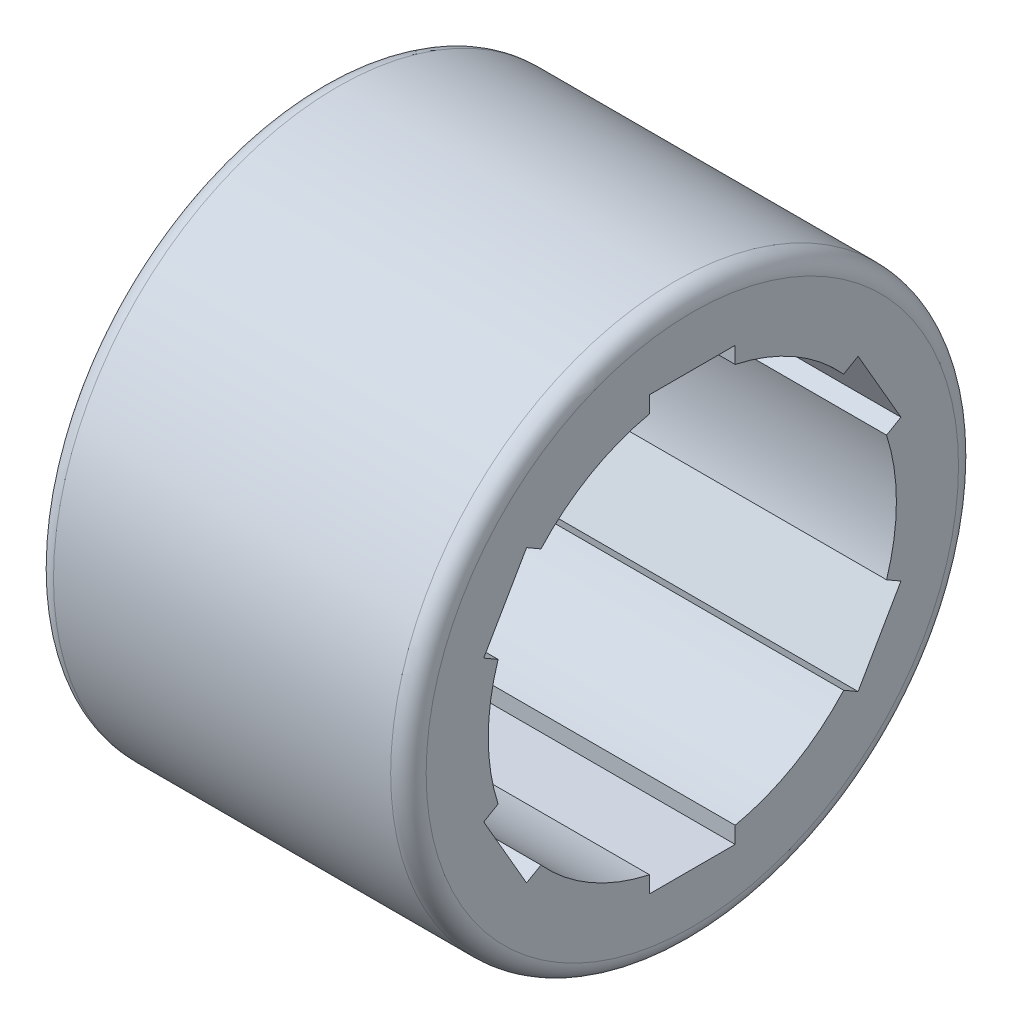
SolidWorks part; units mm, degrees
ref_plane "Front" through (0, 0, 0) normal (0, 0, 1) x (1, 0, 0)
ref_plane "Top" through (0, 0, 0) normal (0, 1, 0) x (1, 0, 0)
ref_plane "Right" through (0, 0, 0) normal (1, 0, 0) x (0, 0, -1)
sketch "Croquis1" plane through (0, 0, 0) normal (1, 0, 0) x (0, 0, -1)
  line L0 (0, 19.3057) -> (0, 12.18) construction
  line L1 (9.3407, 8.1815) -> (11.7557, 3.9985)
  line L3 (-2.415, 11.2436) -> (-2.415, 12.18)
  line L4 (-2.415, 12.18) -> (2.415, 12.18)
  line L5 (2.415, 11.2436) -> (2.415, 12.18)
  line L8 (8.5297, 7.7132) -> (9.3407, 8.1815)
  line L10 (10.9447, 3.5303) -> (11.7557, 3.9985)
  line L11 (11.7557, -3.9985) -> (9.3407, -8.1815)
  line L12 (10.9447, -3.5303) -> (11.7557, -3.9985)
  line L14 (8.5297, -7.7132) -> (9.3407, -8.1815)
  line L15 (2.415, -12.18) -> (-2.415, -12.18)
  line L16 (2.415, -11.2436) -> (2.415, -12.18)
  line L18 (-2.415, -11.2436) -> (-2.415, -12.18)
  line L19 (-9.3407, -8.1815) -> (-11.7557, -3.9985)
  line L20 (-8.5297, -7.7132) -> (-9.3407, -8.1815)
  line L22 (-10.9447, -3.5303) -> (-11.7557, -3.9985)
  line L23 (-11.7557, 3.9985) -> (-9.3407, 8.1815)
  line L24 (-10.9447, 3.5303) -> (-11.7557, 3.9985)
  line L26 (-8.5297, 7.7132) -> (-9.3407, 8.1815)
  arc A0 (-2.415, 11.2436) -> (-8.5297, 7.7132) centre (0, 0) ccw
  circle A1 centre (0, 0) radius 16
  arc A2 (-10.9447, 3.5303) -> (-10.9447, -3.5303) centre (0, 0) ccw
  arc A3 (-8.5297, -7.7132) -> (-2.415, -11.2436) centre (0, 0) ccw
  arc A4 (2.415, -11.2436) -> (8.5297, -7.7132) centre (0, 0) ccw
  arc A5 (10.9447, -3.5303) -> (10.9447, 3.5303) centre (0, 0) ccw
  arc A6 (8.5297, 7.7132) -> (2.415, 11.2436) centre (0, 0) ccw
  point P6 (0, 11.5)
  point P34 (0, 0)
  dimension "D1" = 23
  dimension "D2" = 32
  dimension "D3" = 4.83
  dimension "D5" = 6
extrude "Saliente-Extruir1" add sketch "Croquis1" along normal blind 21
fillet "Redondeo1" radius 1 2 edges at (0, 0, -16) (21, 0, -16)
